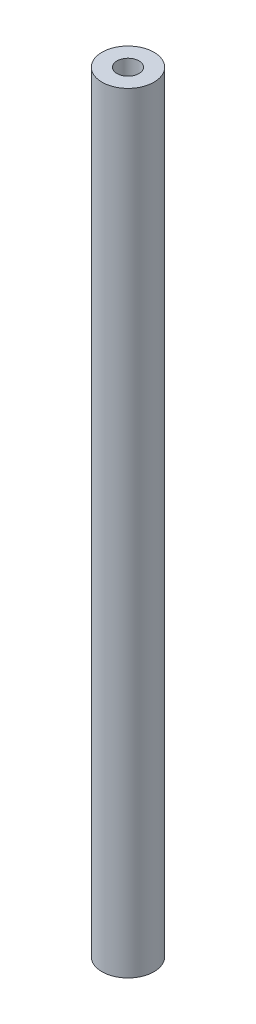
SolidWorks part; units mm, degrees
material "6061 Alloy"
ref_plane "Front Plane" through (0, 0, 0) normal (0, 0, 1) x (1, 0, 0)
ref_plane "Top Plane" through (0, 0, 0) normal (0, 1, 0) x (1, 0, 0)
ref_plane "Right Plane" through (0, 0, 0) normal (1, 0, 0) x (0, 0, -1)
sketch "Sketch1" plane through (0, 0, 0) normal (0, 1, 0) x (1, 0, 0)
  circle A0 centre (0, 0) radius 2.0193
  circle A1 centre (0, 0) radius 4.7625
  dimension "D1" = 4.0386
  dimension "D2" = 9.525
extrude "Boss-Extrude1" add sketch "Sketch1" along normal blind 141.2875
